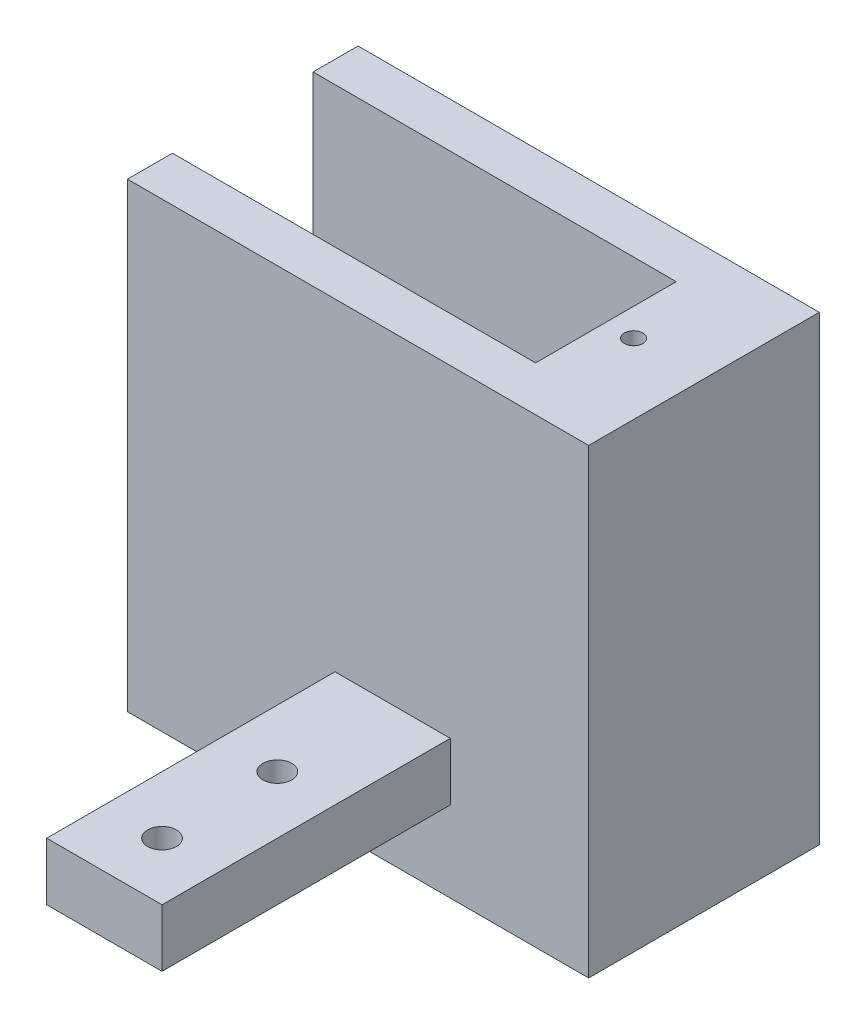
SolidWorks part; units mm, degrees
ref_plane "正面" through (0, 0, 0) normal (0, 0, 1) x (1, 0, 0)
ref_plane "平面" through (0, 0, 0) normal (0, 1, 0) x (1, 0, 0)
ref_plane "右側面" through (0, 0, 0) normal (1, 0, 0) x (0, 0, -1)
sketch "ｽｹｯﾁ2" plane through (0, 0, 0) normal (0, 0, 1) x (1, 0, 0)
  line L1 (-20, 20) -> (20, 20)
  line L2 (-20, 20) -> (-20, -20)
  line L3 (-20, -20) -> (20, -20)
  line L4 (20, 20) -> (20, -20)
  line L5 (-20, 20) -> (20, -20) construction
  line L6 (-20, -20) -> (20, 20) construction
  point P0 (0, 0)
  dimension "D1" = 40
  dimension "D2" = 40
extrude "ﾎﾞｽ - 押し出し1" add sketch "ｽｹｯﾁ2" along normal blind 10
sketch "ｽｹｯﾁ3" plane through (0, 0, 0) normal (0, 0, 1) x (1, 0, 0)
  line L0 (11.5, 20) -> (11.5, 4)
  line L1 (20, 20) -> (-20, 20) construction
  line L2 (11.5, 4) -> (-38.5, 4)
  line L3 (-38.5, 4) -> (-38.5, 20)
  line L4 (-38.5, 20) -> (11.5, 20)
  dimension "D1" = 16
  dimension "D2" = 11.5
  dimension "D3" = 50
extrude "ｶｯﾄ - 押し出し1" cut sketch "ｽｹｯﾁ3" along normal blind 6.1 contours L4 L0 L2 L3
mirror "ﾐﾗｰ1" about plane through (0, 0, 0) normal (0, 0, 1) of "ｶｯﾄ - 押し出し1", "ﾎﾞｽ - 押し出し1"
hole_wizard "M2x0.4 ねじ穴1" positions "ｽｹｯﾁ11" profile "ｽｹｯﾁ10" tap size "M2x0.4" standard "JIS"
sketch "ｽｹｯﾁ11" plane through (0, 20, 0) normal (0, 1, 0) x (1, 0, 0)
  point P0 (13.9, 0)
  point P2 (-13.9, 0)
  dimension "D1" = 13.9
  dimension "D2" = 13.9
cosmetic thread "穴のねじ山6" parameters "D1"=10, "D2"=2
sketch "ｽｹｯﾁ10" plane through (13.9, 20, 0) normal (1, 0, 0) x (0, 0, 1)
  line L0 (0, 0) -> (0, 10.4807)
  line L1 (0, 10.4807) -> (0.8, 10)
  line L2 (0.8, 10) -> (0.8, 0)
  line L5 (0.8, 0) -> (0, 0)
  line L10 (0, 10.4807) -> (-0.8, 10) construction
  line L11 (0, -6.35) -> (0, 107.95) construction
  dimension "ねじ下穴ﾄﾞﾘﾙ直径" = 1.6
  dimension "ねじ下穴ﾄﾞﾘﾙの深さ" = 10
  dimension "ﾄﾞﾘﾙ角度" = 118
ref_plane "平面3" through (0, 0, -10) normal (0, 0, -1) x (-1, 0, 0)
sketch "ｽｹｯﾁ12" plane through (0, 0, -10) normal (0, 0, -1) x (-1, 0, 0)
  line L0 (14, 20) -> (14, 15)
  line L1 (-20, 20) -> (20, 20) construction
  line L2 (14, 15) -> (4, 15)
  line L3 (4, 15) -> (4, 20)
  line L4 (4, 20) -> (14, 20)
  line L5 (20, 20) -> (20, -20) construction
  dimension "D1" = 5
  dimension "D2" = 10
  dimension "D3" = 6
ref_plane "平面4" through (0, 0, 10) normal (0, 0, 1) x (1, 0, 0)
sketch "ｽｹｯﾁ13" plane through (0, 0, 10) normal (0, 0, 1) x (1, 0, 0)
  line L0 (8, -8) -> (-2, -8)
  line L1 (-2, -8) -> (-2, -13)
  line L2 (-2, -13) -> (8, -13)
  line L3 (8, -13) -> (8, -8)
  line L4 (20, 20) -> (-20, 20) construction
  line L5 (-20, 20) -> (-20, -20) construction
  dimension "D1" = 28
  dimension "D2" = 5
  dimension "D3" = 10
  dimension "D4" = 18
extrude "ﾎﾞｽ - 押し出し5" add sketch "ｽｹｯﾁ13" along normal blind 25
hole_wizard "M3x0.5 ねじ穴2" positions "ｽｹｯﾁ14" profile "ｽｹｯﾁ15" tap size "M3x0.5" standard "JIS"
sketch "ｽｹｯﾁ14" plane through (0, -13, 0) normal (0, -1, 0) x (-1, 0, 0)
  line L0 (-8, -35) -> (-8, -10) construction
  line L1 (-22, -10) -> (22, -10) construction
  point P0 (-3, -20)
  point P2 (-3, -30)
  dimension "D1" = 5
  dimension "D2" = 5
  dimension "D3" = 10
  dimension "D4" = 10
sketch "ｽｹｯﾁ15" plane through (3, -13, 20) normal (1, 0, 0) x (0, 0, -1)
  line L0 (0, 0) -> (0, 9.2511)
  line L1 (0, 9.2511) -> (1.25, 8.5)
  line L2 (1.25, 8.5) -> (1.25, 0)
  line L5 (1.25, 0) -> (0, 0)
  line L10 (0, 9.2511) -> (-1.25, 8.5) construction
  line L11 (0, -6.35) -> (0, 107.95) construction
  dimension "ねじ下穴ﾄﾞﾘﾙ直径" = 2.5
  dimension "ねじ下穴ﾄﾞﾘﾙの深さ" = 8.5
  dimension "ﾄﾞﾘﾙ角度" = 118
cosmetic thread "穴のねじ山7" parameters "D1"=6, "D2"=3
cosmetic thread "穴のねじ山8" parameters "D1"=6, "D2"=3
hole_wizard "M3x0.5 ねじ穴1" [suppressed] positions "ｽｹｯﾁ4" profile "ｽｹｯﾁ5" tap size "M3x0.5" standard "JIS"
sketch "ｽｹｯﾁ4" plane through (0, 0, 0) normal (0, 0, -1) x (-1, 0, 0)
  line L0 (11.5, 25) -> (25, 25) construction
  line L1 (-25, 25) -> (-11.5, 25) construction
  point P0 (18, 15)
  point P2 (-18, 15)
  point P4 (-18, -15)
  point P6 (18, -15)
  dimension "D1" = 18
  dimension "D2" = 18
  dimension "D3" = 18
  dimension "D4" = 18
  dimension "D5" = 30
  dimension "D6" = 30
  dimension "D7" = 10
  dimension "D8" = 10
sketch "ｽｹｯﾁ5" plane through (-18, 15, 0) normal (1, 0, 0) x (0, 1, 0)
  line L0 (0, 0) -> (0, 10)
  line L1 (0, 10) -> (1.25, 10)
  line L2 (1.25, 10) -> (1.25, 0)
  line L5 (1.25, 0) -> (0, 0)
  line L11 (0, -6.35) -> (0, 107.95) construction
  dimension "次ｻｰﾌｪｽまでのねじ下穴ﾄﾞﾘﾙ直径" = 2.5
  dimension "次ｻｰﾌｪｽまでのねじ下穴ﾄﾞﾘﾙの深さ" = 10
cosmetic thread "穴のねじ山1" parameters "D2"=3
cosmetic thread "穴のねじ山2" parameters "D2"=3
cosmetic thread "穴のねじ山3" parameters "D2"=3
cosmetic thread "穴のねじ山4" parameters "D2"=3
ref_plane "平面1" through (0, 0, 10) normal (0, 0, 1) x (1, 0, 0)
sketch "ｽｹｯﾁ6" plane through (0, 0, 10) normal (0, 0, 1) x (1, 0, 0)
  line L1 (-5, 5) -> (5, 5)
  line L2 (-5, 5) -> (-5, -5)
  line L3 (-5, -5) -> (5, -5)
  line L4 (5, 5) -> (5, -5)
  line L5 (-5, 5) -> (5, -5) construction
  line L6 (-5, -5) -> (5, 5) construction
  point P0 (0, 0)
  dimension "D1" = 10
  dimension "D2" = 10
extrude "ﾎﾞｽ - 押し出し2" [suppressed] add sketch "ｽｹｯﾁ6" along normal blind 30
ref_plane "平面2" [suppressed] through (5, 0, 0) normal (1, 0, 0) x (0, 0, -1)
sketch "ｽｹｯﾁ8" [suppressed] plane through (5, 0, 0) normal (1, 0, 0) x (0, 0, -1)
  line L0 (-10, 27.5) -> (-10, -27.5) construction
  circle A0 centre (-52, 0) radius 15
  dimension "D1" = 30
  dimension "D2" = 42
extrude "ﾎﾞｽ - 押し出し3" [suppressed] add sketch "ｽｹｯﾁ8" against normal blind 10
